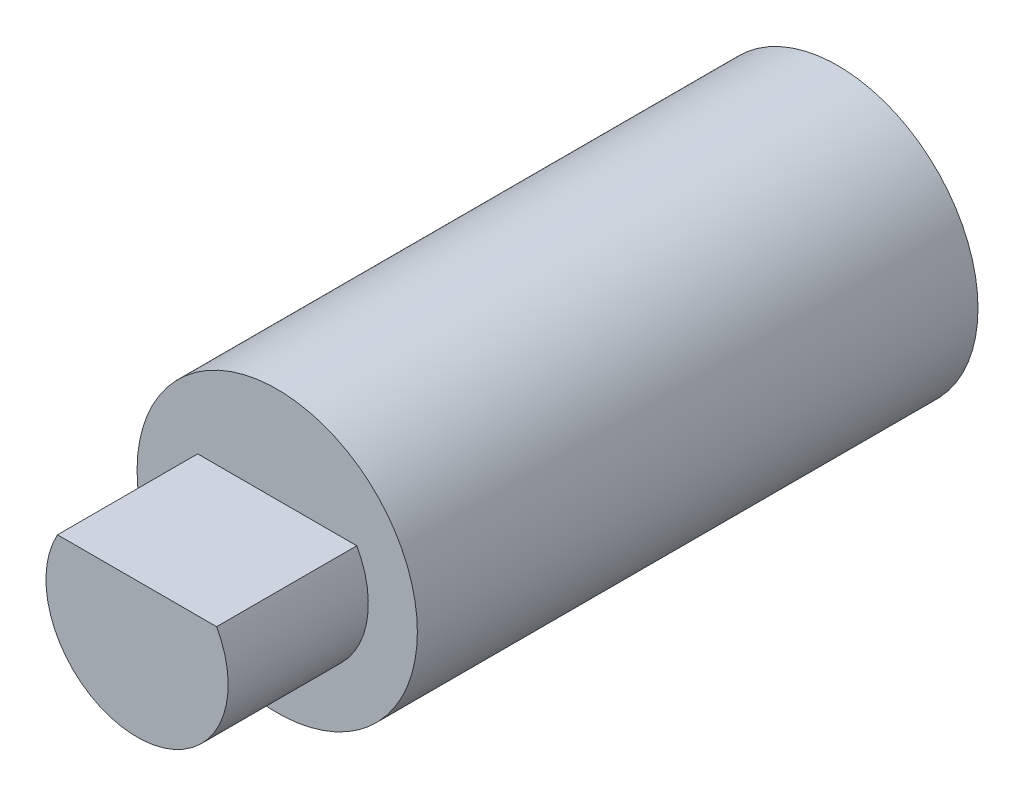
SolidWorks part; units mm, degrees
ref_plane "Front Plane" through (0, 0, 0) normal (0, 0, 1) x (1, 0, 0)
ref_plane "Top Plane" through (0, 0, 0) normal (0, 1, 0) x (1, 0, 0)
ref_plane "Right Plane" through (0, 0, 0) normal (1, 0, 0) x (0, 0, -1)
sketch "Sketch1" plane through (0, 0, 0) normal (0, 0, 1) x (1, 0, 0)
  line L0 (-1.1619, 1.1) -> (1.1619, 1.1)
  arc A0 (-1.1619, 1.1) -> (1.1619, 1.1) centre (0, 0) ccw
  circle A1 centre (0, 0) radius 3
  point P5 (0, -1.6)
  dimension "D1" = 3.2
  dimension "D3" = 6
  dimension "D2" = 2.7
extrude "Boss-Extrude1" add sketch "Sketch1" along normal blind 10
sketch "Sketch2" plane through (0, 0, 10) normal (0, 0, 1) x (1, 0, 0)
  circle A0 centre (0, 0) radius 3
extrude "Boss-Extrude2" add sketch "Sketch2" along normal blind 2
sketch "Sketch3" plane through (0, 0, 12) normal (0, 0, 1) x (1, 0, 0)
  line L0 (-1.7029, 0.95) -> (1.7029, 0.95)
  arc A0 (-1.7029, 0.95) -> (1.7029, 0.95) centre (0, 0) ccw
  point P5 (0, -1.95)
  dimension "D1" = 3.9
  dimension "D2" = 2.9
extrude "Boss-Extrude3" add sketch "Sketch3" along normal blind 3
